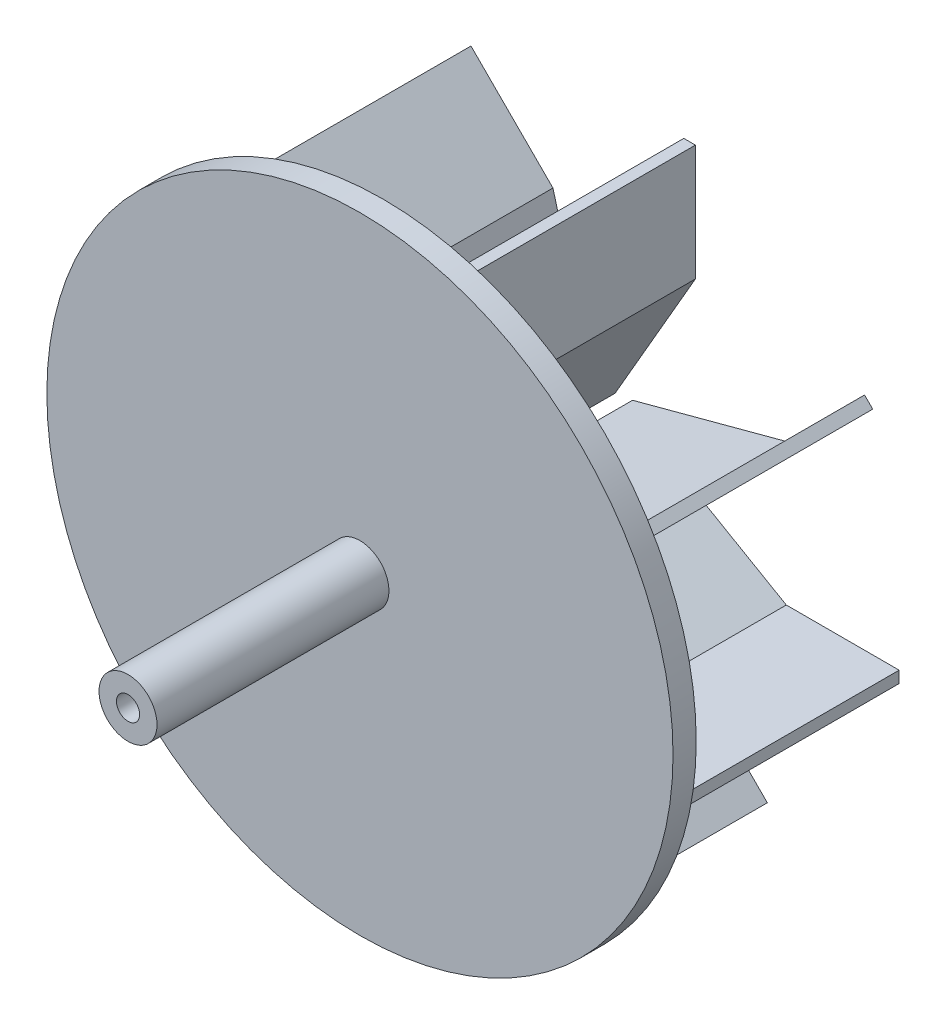
SolidWorks part; units mm, degrees
ref_plane "前视基准面" through (0, 0, 0) normal (0, 0, 1) x (1, 0, 0)
ref_plane "上视基准面" through (0, 0, 0) normal (0, 1, 0) x (1, 0, 0)
ref_plane "右视基准面" through (0, 0, 0) normal (1, 0, 0) x (0, 0, -1)
sketch "草图1" plane through (0, 0, 0) normal (0, 0, 1) x (1, 0, 0)
  circle A0 centre (0, 0) radius 27
  dimension "D1" = 54
extrude "凸台-拉伸1" add sketch "草图1" along normal blind 2
sketch "草图2" plane through (0, 0, 0) normal (0, 0, 1) x (1, 0, 0)
  line L0 (0, 0) -> (-2.5, 0) construction
  line L1 (-2.5, 0) -> (-14.5, 6.9282)
  line L2 (-14.5, 6.9282) -> (-24.5, 6.9282)
  line L3 (-3, -0.866) -> (-14.7679, 5.9282)
  line L4 (-14.7679, 5.9282) -> (-24.5, 5.9282)
  line L5 (-2.5, 0) -> (-3, -0.866)
  line L6 (-24.5, 6.9282) -> (-24.5, 5.9282)
  line L7 (-12.4251, 22.2231) -> (-13.1322, 21.516)
  line L8 (-6.2506, 14.6344) -> (-13.1322, 21.516)
  line L9 (-2.7337, 1.5089) -> (-6.2506, 14.6344)
  line L10 (-1.7678, 1.7678) -> (-2.7337, 1.5089)
  line L11 (-1.7678, 1.7678) -> (-5.3541, 15.152)
  line L12 (-5.3541, 15.152) -> (-12.4251, 22.2231)
  line L13 (6.9282, 24.5) -> (5.9282, 24.5)
  line L14 (5.9282, 14.7679) -> (5.9282, 24.5)
  line L15 (-0.866, 3) -> (5.9282, 14.7679)
  line L16 (0, 2.5) -> (-0.866, 3)
  line L17 (0, 2.5) -> (6.9282, 14.5)
  line L18 (6.9282, 14.5) -> (6.9282, 24.5)
  line L19 (22.2231, 12.4251) -> (21.516, 13.1322)
  line L20 (14.6344, 6.2506) -> (21.516, 13.1322)
  line L21 (1.5089, 2.7337) -> (14.6344, 6.2506)
  line L22 (1.7678, 1.7678) -> (1.5089, 2.7337)
  line L23 (1.7678, 1.7678) -> (15.152, 5.3541)
  line L24 (15.152, 5.3541) -> (22.2231, 12.4251)
  line L25 (24.5, -6.9282) -> (24.5, -5.9282)
  line L26 (14.7679, -5.9282) -> (24.5, -5.9282)
  line L27 (3, 0.866) -> (14.7679, -5.9282)
  line L28 (2.5, 0) -> (3, 0.866)
  line L29 (2.5, 0) -> (14.5, -6.9282)
  line L30 (14.5, -6.9282) -> (24.5, -6.9282)
  line L31 (12.4251, -22.2231) -> (13.1322, -21.516)
  line L32 (6.2506, -14.6344) -> (13.1322, -21.516)
  line L33 (2.7337, -1.5089) -> (6.2506, -14.6344)
  line L34 (1.7678, -1.7678) -> (2.7337, -1.5089)
  line L35 (1.7678, -1.7678) -> (5.3541, -15.152)
  line L36 (5.3541, -15.152) -> (12.4251, -22.2231)
  line L37 (-6.9282, -24.5) -> (-5.9282, -24.5)
  line L38 (-5.9282, -14.7679) -> (-5.9282, -24.5)
  line L39 (0.866, -3) -> (-5.9282, -14.7679)
  line L40 (0, -2.5) -> (0.866, -3)
  line L41 (0, -2.5) -> (-6.9282, -14.5)
  line L42 (-6.9282, -14.5) -> (-6.9282, -24.5)
  line L43 (-22.2231, -12.4251) -> (-21.516, -13.1322)
  line L44 (-14.6344, -6.2506) -> (-21.516, -13.1322)
  line L45 (-1.5089, -2.7337) -> (-14.6344, -6.2506)
  line L46 (-1.7678, -1.7678) -> (-1.5089, -2.7337)
  line L47 (-1.7678, -1.7678) -> (-15.152, -5.3541)
  line L48 (-15.152, -5.3541) -> (-22.2231, -12.4251)
  point P53 (0, 0)
  dimension "D1" = 2.5
  dimension "D2" = 150
  dimension "D3" = 12
  dimension "D4" = 10
  dimension "D5" = 1
  dimension "D6" = 8
extrude "凸台-拉伸2" add sketch "草图2" against normal blind 20
sketch "草图3" plane through (0, 0, 2) normal (0, 0, 1) x (1, 0, 0)
  circle A0 centre (0, 0) radius 2.5
extrude "凸台-拉伸3" add sketch "草图3" along normal blind 20
sketch "草图4" plane through (0, 0, 22) normal (0, 0, 1) x (1, 0, 0)
  circle A0 centre (0, 0) radius 1
extrude "切除-拉伸1" cut sketch "草图4" against normal blind 15
